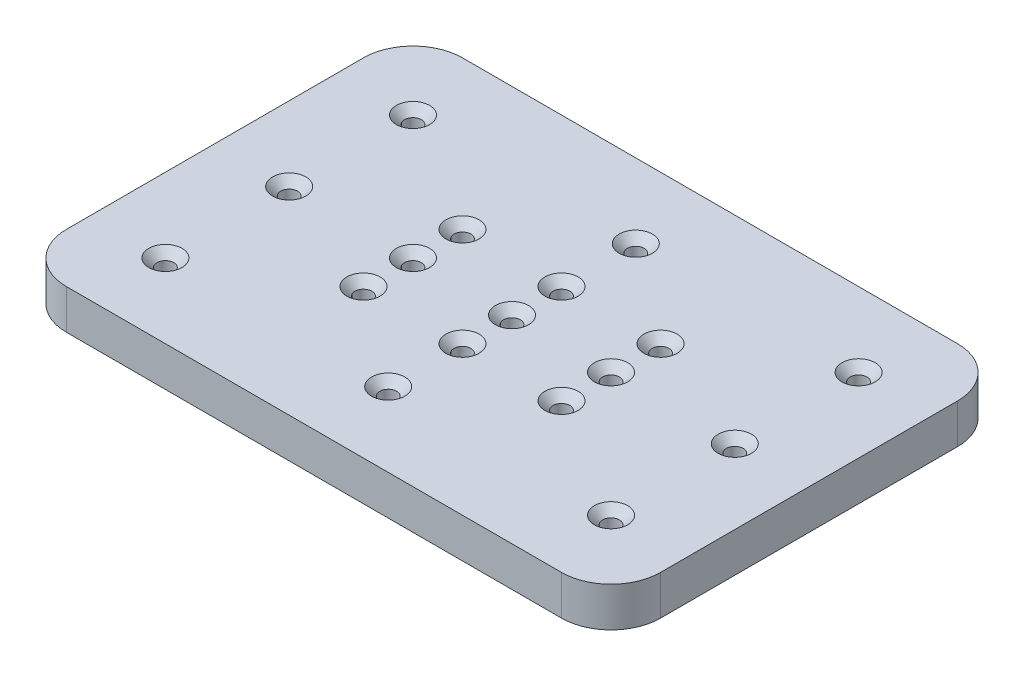
SolidWorks part; units mm, degrees
material "1060 Alloy"
ref_plane "Front Plane" through (0, 0, 0) normal (0, 0, 1) x (1, 0, 0)
ref_plane "Top Plane" through (0, 0, 0) normal (0, 1, 0) x (1, 0, 0)
ref_plane "Right Plane" through (0, 0, 0) normal (1, 0, 0) x (0, 0, -1)
sketch "Sketch3" plane through (0, 0, 0) normal (0, 1, 0) x (1, 0, 0)
  line L1 (-50, 40) -> (50, 40)
  line L2 (-60, 30) -> (-60, -30)
  line L3 (-50, -40) -> (50, -40)
  line L4 (60, 30) -> (60, -30)
  line L5 (-60, 40) -> (60, -40) construction
  line L6 (-60, -40) -> (60, 40) construction
  arc A0 (-60, -30) -> (-50, -40) centre (-50, -30) ccw
  arc A1 (50, -40) -> (60, -30) centre (50, -30) ccw
  arc A2 (50, 40) -> (60, 30) centre (50, 30) cw
  arc A3 (-50, 40) -> (-60, 30) centre (-50, 30) ccw
  point P0 (0, 0)
  dimension "D3" = 10
  dimension "D1" = 120
  dimension "D2" = 80
extrude "Boss-Extrude2" add sketch "Sketch3" along normal blind 8
sketch "Sketch4" plane through (0, 8, 0) normal (0, 1, 0) x (1, 0, 0)
  line L0 (-68.1697, 0) -> (81.1427, 0) construction
  line L1 (0, 42.652) -> (0, -46.9355) construction
  point P0 (0, 0)
  point P1 (0, 10)
  point P3 (0, 25)
  point P4 (20, 10)
  point P5 (20, 0)
  point P6 (45, 0)
  point P7 (45, 25)
  point P12 (-45, 25)
  point P13 (-45, 0)
  point P14 (-20, 10)
  point P15 (-20, 0)
  point P16 (-20, -10)
  point P17 (-45, -25)
  point P18 (45, -25)
  point P19 (20, -10)
  point P20 (0, -25)
  point P21 (0, -10)
  point P22 (45, -34.2072)
  dimension "D1" = 10
  dimension "D2" = 25
  dimension "D3" = 20
  dimension "D4" = 45
hole_wizard "CSK for M3 Hex Socket Countersunk Cap Screw1" positions "Sketch4" profile "Sketch5" countersink size "M3" standard "ISO" end condition through all
sketch "Sketch5" plane through (0, 8, 0) normal (1, 0, 0) x (0, 0, 1)
  line L0 (0, 0) -> (0, 8)
  line L1 (0, 8) -> (1.7, 8)
  line L2 (1.7, 8) -> (1.7, 1.66)
  line L3 (1.7, 1.66) -> (3.36, 0)
  line L5 (3.36, 0) -> (0, 0)
  line L6 (-1.7, 1.66) -> (-3.36, 0) construction
  line L11 (0, -6.35) -> (0, 107.95) construction
  dimension "Thru Hole Dia." = 3.4
  dimension "Thru Hole Depth" = 8
  dimension "Near C'Sink Dia." = 6.72
  dimension "Near C'Sink Angle" = 90
